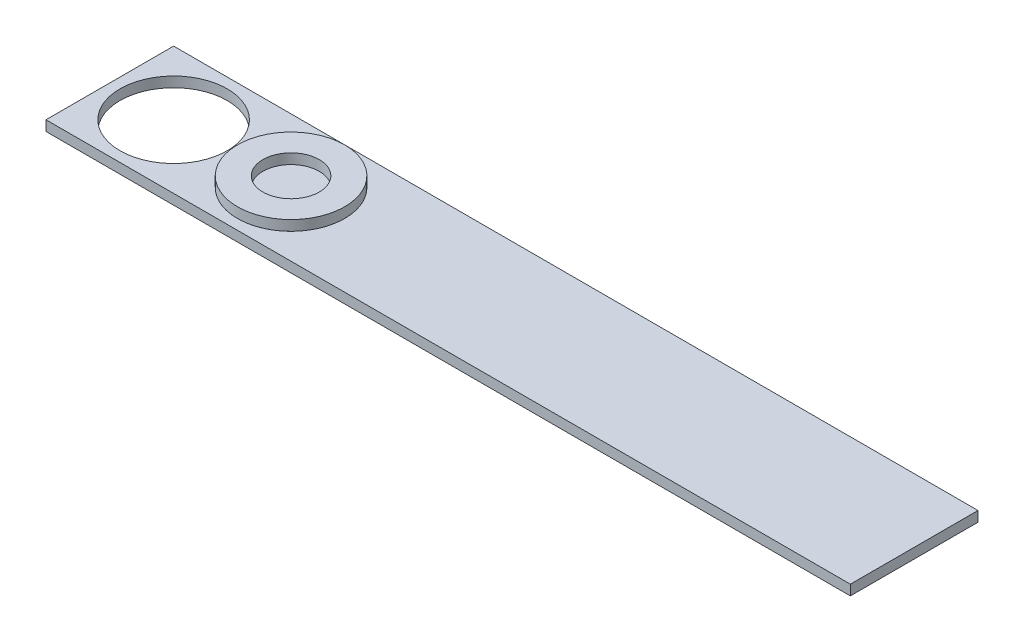
SolidWorks part; units mm, degrees
material "Galvanized Steel"
ref_plane "Front Plane" through (0, 0, 0) normal (0, 0, 1) x (1, 0, 0)
ref_plane "Top Plane" through (0, 0, 0) normal (0, 1, 0) x (1, 0, 0)
ref_plane "Right Plane" through (0, 0, 0) normal (1, 0, 0) x (0, 0, -1)
sketch "Sketch1" plane through (0, 0, 0) normal (0, 1, 0) x (1, 0, 0)
  line L1 (-75, -11.9) -> (75, -11.9)
  line L2 (-75, -11.9) -> (-75, 11.9)
  line L3 (-75, 11.9) -> (75, 11.9)
  line L4 (75, -11.9) -> (75, 11.9)
  line L5 (-75, -11.9) -> (75, 11.9) construction
  line L6 (-75, 11.9) -> (75, -11.9) construction
  point P0 (0, 0)
  dimension "D1" = 23.8
  dimension "D2" = 150
extrude "Boss-Extrude1" add sketch "Sketch1" along normal mid plane 1.9
ref_plane "Plane1" through (0, 1.9, 0) normal (0, 1, 0) x (1, 0, 0)
ref_plane "Plane2" through (0, 0, 0) normal (0, 1, 0) x (1, 0, 0)
sketch "Sketch6" plane through (0, 0.95, 0) normal (0, 1, 0) x (1, 0, 0)
  line L0 (-75, 11.9) -> (-75, -11.9) construction
  circle A0 centre (-63.1, 0) radius 10
  dimension "D1" = 1.9
  dimension "D2" = 20
extrude "Cut-Extrude2" cut sketch "Sketch6" against normal up to next
sketch "Sketch3" plane through (0, 0.95, 0) normal (0, 1, 0) x (1, 0, 0)
  line L0 (-1.045, 0) -> (1.045, 0) construction
  line L1 (-75, 11.9) -> (-75, -11.9) construction
  circle A0 centre (-41.2, 0) radius 10
  dimension "D1" = 23.8
  dimension "D2" = 20
extrude "Cut-Extrude1" cut sketch "Sketch3" against normal up to next
sketch "Sketch4" plane through (0, 1.9, 0) normal (0, 1, 0) x (1, 0, 0)
  circle A0 centre (-41.2, 0) radius 10 construction
  circle A1 centre (-41.2, 0) radius 10
  circle A2 centre (-41.2, 0) radius 5.25
  dimension "D1" = 10.5
extrude "Boss-Extrude3" add sketch "Sketch4" along normal mid plane 1.9 separate body
sketch "Sketch5" plane through (0, 0, 0) normal (0, 1, 0) x (1, 0, 0)
  circle A0 centre (-41.2, 0) radius 5.25 construction
  circle A1 centre (-41.2, 0) radius 5.25
extrude "Boss-Extrude4" add sketch "Sketch5" along normal mid plane 1.9 separate body
